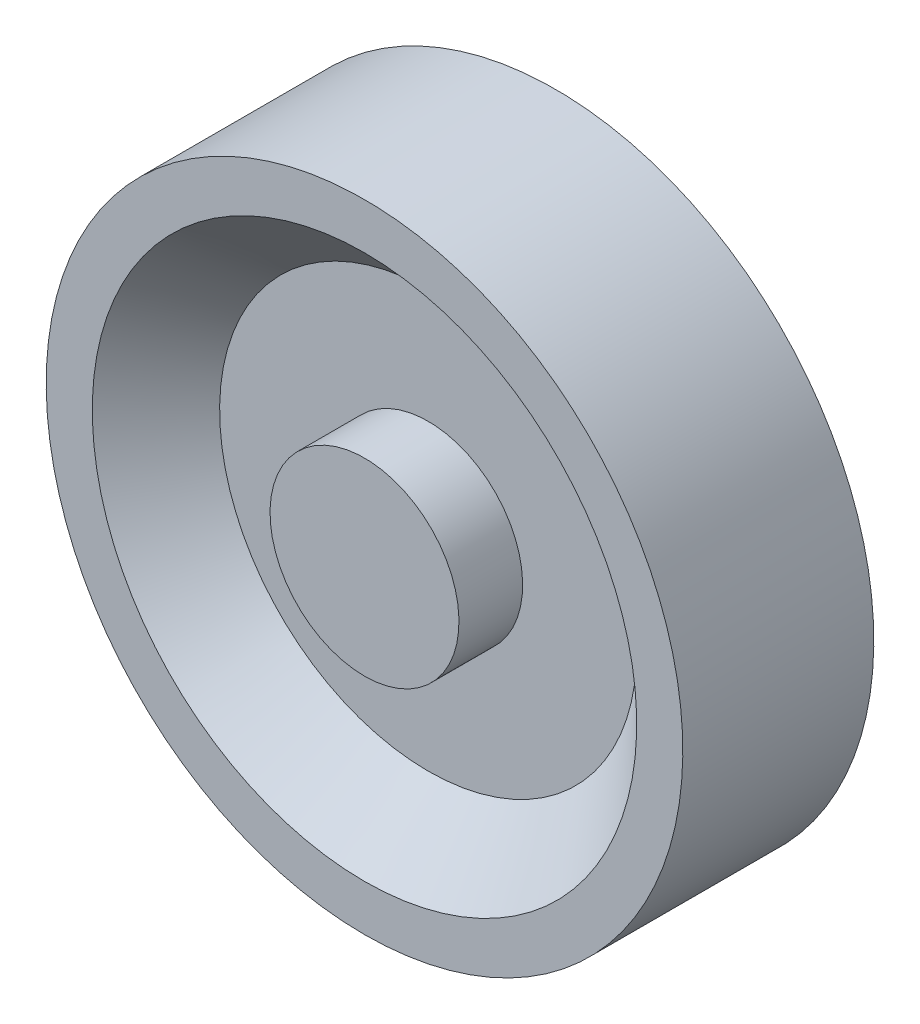
SolidWorks part; units mm, degrees
ref_plane "Front Plane" through (0, 0, 0) normal (0, 0, 1) x (1, 0, 0)
ref_plane "Top Plane" through (0, 0, 0) normal (0, 1, 0) x (1, 0, 0)
ref_plane "Right Plane" through (0, 0, 0) normal (1, 0, 0) x (0, 0, -1)
sketch "Sketch2" plane through (0, 0, 0) normal (1, 0, 0) x (0, 0, -1)
  line L0 (0, 0) -> (3, 0)
  line L1 (15, 3) -> (15, 7.42)
  line L2 (15, 25) -> (0, 25)
  line L3 (0, 25) -> (0, 21.38)
  line L4 (15, 3) -> (3, 3)
  line L5 (3, 3) -> (3, 0)
  line L6 (15, 7.42) -> (10, 7.42)
  line L7 (10, 7.42) -> (10, 16.38)
  line L8 (10, 16.38) -> (15, 21.38)
  line L9 (0, 7.42) -> (5, 7.42)
  line L10 (5, 7.42) -> (5, 16.38)
  line L11 (5, 16.38) -> (0, 21.38)
  line L12 (0, 7.42) -> (0, 0)
  line L13 (15, 21.38) -> (15, 25)
  point P1 (1.5, 0)
  dimension "D2" = 7.42
  dimension "D3" = 3
  dimension "D4" = 21.38
  dimension "D5" = 135
  dimension "D6" = 25
  dimension "D7" = 21.38
  dimension "D9" = 5
  dimension "D10" = 12
  dimension "D11" = 135
  dimension "D12" = 3
  dimension "D13" = 5
revolve "Revolve1" add sketch "Sketch2" angle 360 about L0
